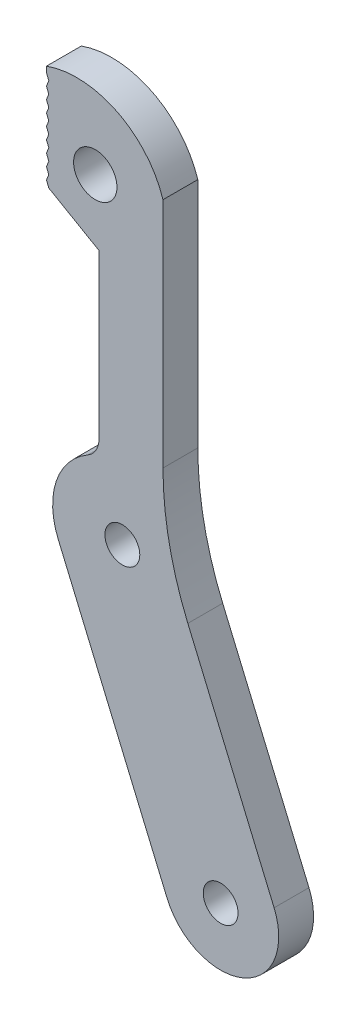
SolidWorks part; units mm, degrees
ref_plane "Front Plane" through (0, 0, 0) normal (0, 0, 1) x (1, 0, 0)
ref_plane "Top Plane" through (0, 0, 0) normal (0, 1, 0) x (1, 0, 0)
ref_plane "Right Plane" through (0, 0, 0) normal (1, 0, 0) x (0, 0, -1)
sketch "Sketch1" plane through (0, 0, 0) normal (0, 0, 1) x (1, 0, 0)
  line L0 (19.9553, -21.6867) -> (19.9553, -7.6867)
  line L1 (19.9553, -7.6867) -> (15.6252, -5.1867)
  line L2 (15.4252, -4.6867) -> (15.6252, -5.1867)
  line L3 (15.4252, -4.6867) -> (15.6252, -4.1867)
  line L4 (16.4357, -30.9581) -> (25.8159, -53.0491)
  line L5 (35.0205, -49.1407) -> (27.5945, -31.652)
  line L6 (25.4553, -21.1407) -> (25.4553, -1.1407)
  line L7 (15.4252, 3.3133) -> (15.4252, 3.8022)
  line L8 (15.4252, -3.6867) -> (15.6252, -4.1867)
  line L9 (15.4252, -3.6867) -> (15.6252, -3.1867)
  line L10 (15.4252, -2.6867) -> (15.6252, -3.1867)
  line L11 (15.4252, -2.6867) -> (15.6252, -2.1867)
  line L12 (15.4252, -1.6867) -> (15.6252, -2.1867)
  line L13 (15.4252, -1.6867) -> (15.6252, -1.1867)
  line L14 (15.4252, -0.6867) -> (15.6252, -1.1867)
  line L15 (15.4252, -0.6867) -> (15.6252, -0.1867)
  line L16 (15.4252, 0.3133) -> (15.6252, -0.1867)
  line L17 (15.4252, 0.3133) -> (15.6252, 0.8133)
  line L18 (15.4252, 1.3133) -> (15.6252, 0.8133)
  line L19 (15.4252, 1.3133) -> (15.6252, 1.8133)
  line L20 (15.4252, 2.3133) -> (15.6252, 1.8133)
  line L21 (15.4252, 2.3133) -> (15.6252, 2.8133)
  line L22 (15.4252, 3.3133) -> (15.6252, 2.8133)
  line L24 (15.4252, 3.3133) -> (15.6252, 3.8133) [skipped]
  arc A0 (19.9553, -21.6867) -> (18.9561, -23.4182) centre (17.9553, -21.6867) cw
  arc A1 (18.9561, -23.4182) -> (16.4357, -30.9581) centre (21.9585, -28.613) ccw
  arc A2 (25.8159, -53.0491) -> (35.0205, -49.1407) centre (30.4182, -51.0949) ccw
  arc A3 (27.5945, -31.652) -> (25.4553, -21.1407) centre (52.3494, -21.1407) cw
  arc A4 (15.4252, 3.8022) -> (25.4553, -1.1407) centre (18.0464, -3.527) cw
  circle A5 centre (30.4182, -51.0949) radius 1.5
  circle A6 centre (19.6252, -2.1867) radius 1.8668
  circle A7 centre (21.9585, -28.613) radius 1.5
  point P29 (15.4252, 3.8022)
  dimension "D1" = 14
  dimension "D3" = 2
  dimension "D4" = 6
  dimension "D6" = 24
  dimension "D8" = 48
  dimension "D10" = 26.8941
  dimension "D14" = 1
  dimension "D16" = 3
  dimension "D17" = 4
  dimension "D18" = 3
  dimension "D2" = 5.5
  dimension "D5" = 10
  dimension "D7" = 20
  dimension "D9" = 19
  dimension "D11" = 5
  dimension "D12" = 0.5385
  dimension "D13" = 120
  dimension "D15" = 9
extrude "Boss-Extrude2" add sketch "Sketch1" along normal blind 3
